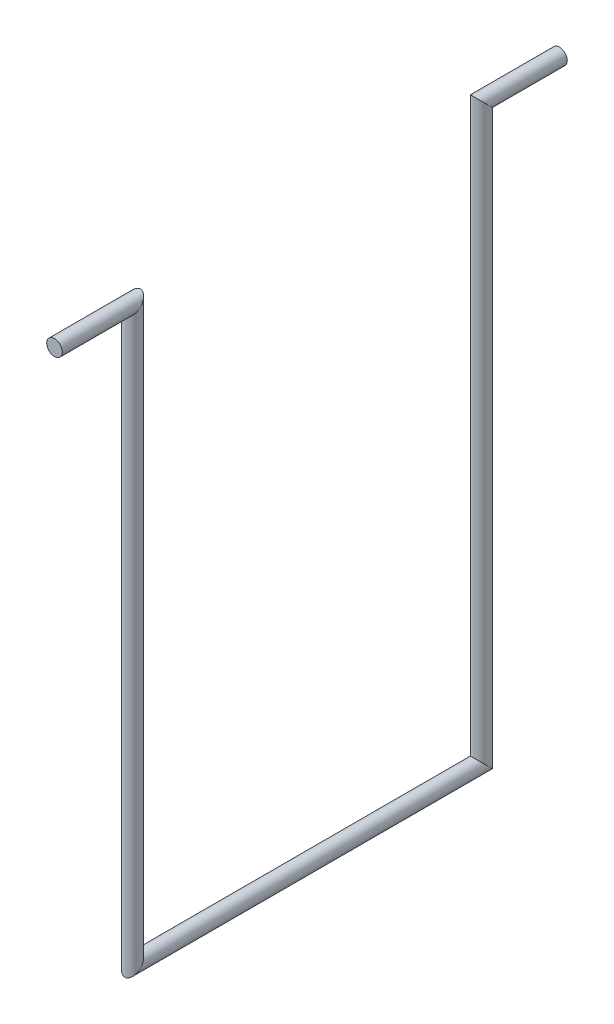
SolidWorks part; units mm, degrees
ref_plane "Front Plane" through (0, 0, 0) normal (0, 0, 1) x (1, 0, 0)
ref_plane "Top Plane" through (0, 0, 0) normal (0, 1, 0) x (1, 0, 0)
ref_plane "Right Plane" through (0, 0, 0) normal (1, 0, 0) x (0, 0, -1)
sketch "Sketch1" plane through (0, 0, 0) normal (1, 0, 0) x (0, 0, -1)
  line L0 (0, 0) -> (0, -55)
  line L1 (0, -55) -> (33.5, -55)
  line L2 (33.5, -55) -> (33.5, 0)
  line L3 (33.5, 0) -> (41, 0)
  line L4 (0, 0) -> (-7.5, 0)
  dimension "D1" = 55
  dimension "D2" = 33.5
  dimension "D3" = 7.5
  dimension "D4" = 7.5
ref_plane "Plane1" through (0, 0, 7.5) normal (0, 0, 1) x (1, 0, 0)
sketch "Sketch2" plane through (0, 0, 7.5) normal (0, 0, 1) x (1, 0, 0)
  circle A0 centre (0, 0) radius 0.75
  dimension "D1" = 1.5
sweep "Sweep1" add profiles "Sketch2" path "Sketch1"
